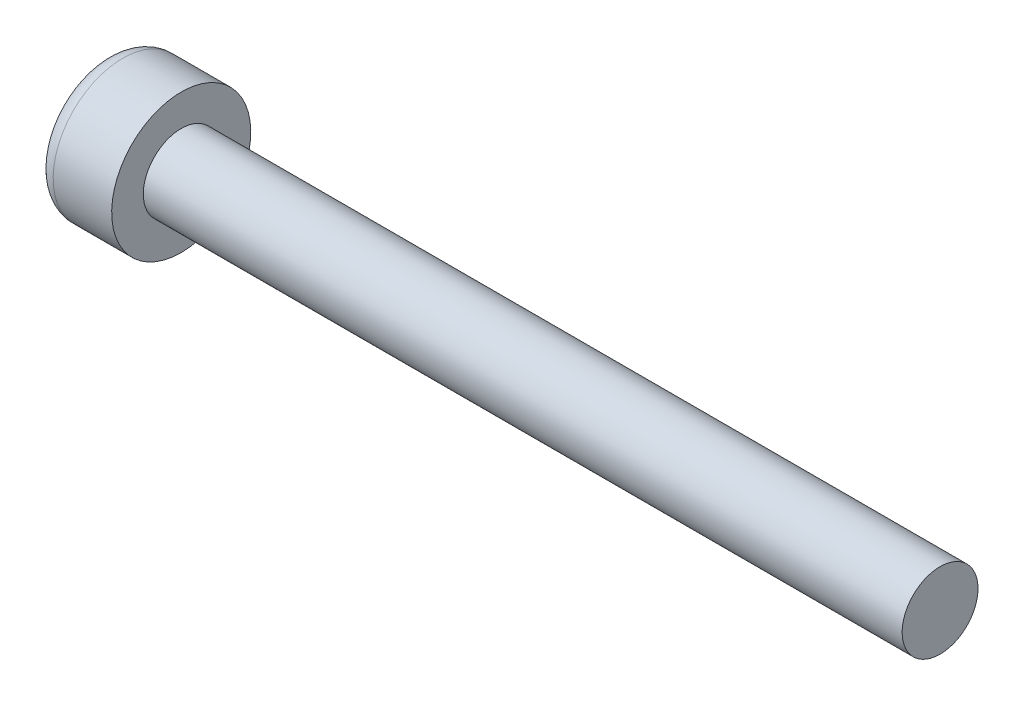
SolidWorks part; units mm, degrees
material "Plain Carbon Steel"
ref_plane "Front Plane" through (0, 0, 0) normal (0, 0, 1) x (1, 0, 0)
ref_plane "Top Plane" through (0, 0, 0) normal (0, 1, 0) x (1, 0, 0)
ref_plane "Right Plane" through (0, 0, 0) normal (1, 0, 0) x (0, 0, -1)
sketch "Sketch1" plane through (0, 0, 0) normal (0, 0, 1) x (1, 0, 0)
  line L0 (0, 0) -> (0, 2.0625)
  line L1 (0.6875, 2.75) -> (3, 2.75)
  line L2 (3, 2.75) -> (3, 1.5)
  line L3 (3, 1.5) -> (33, 1.5)
  line L4 (33, 1.5) -> (33, 0)
  line L5 (33, 0) -> (0, 0) construction
  line L6 (0.6875, 2.0625) -> (0.6875, 1.375) construction
  line L7 (0.6875, 1.375) -> (0.6875, 0.6875) construction
  line L8 (0.6875, 0.6875) -> (0.6875, 0) construction
  line L9 (0.6875, 2.75) -> (0.6875, 2.0625) construction
  line L10 (0, 0) -> (33, 0)
  arc A0 (0, 2.0625) -> (0.6875, 2.75) centre (0.6875, 2.0625) cw
  dimension "D1" = 3
  dimension "D2" = 5.5
  dimension "D3" = 3
  dimension "D4" = 30
revolve "Revolve1" add sketch "Sketch1" angle 360 about L10
sketch "Sketch2" plane through (0, 0, 0) normal (-1, 0, 0) x (0, 0, 1)
  line L1 (0, 1.4434) -> (-1.25, 0.7217)
  line L2 (-1.25, 0.7217) -> (-1.25, -0.7217)
  line L3 (-1.25, -0.7217) -> (0, -1.4434)
  line L4 (0, -1.4434) -> (1.25, -0.7217)
  line L5 (1.25, -0.7217) -> (1.25, 0.7217)
  line L6 (1.25, 0.7217) -> (0, 1.4434)
  circle A0 centre (0, 0) radius 1.25 construction
  dimension "D1" = 2.5
extrude "Cut-Extrude1" cut sketch "Sketch2" against normal blind 1.5
